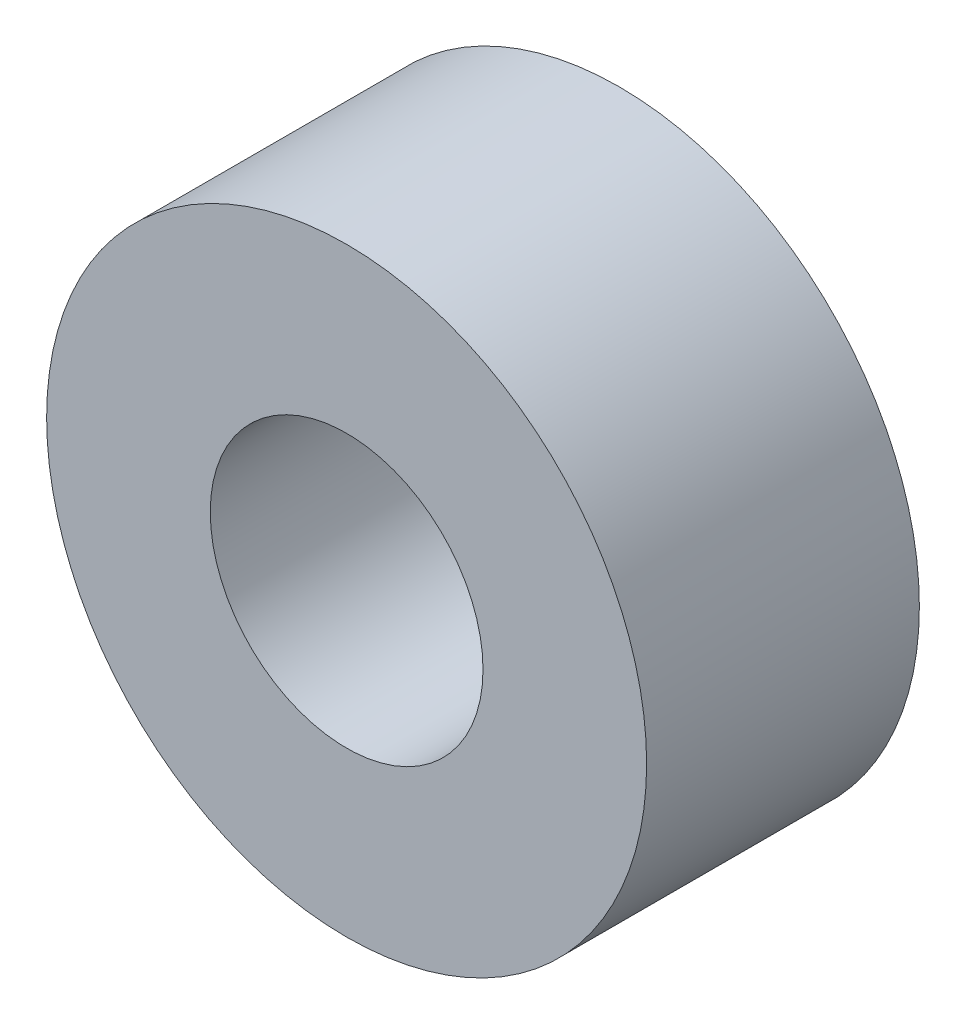
SolidWorks part; units mm, degrees
ref_plane "Front" through (0, 0, 0) normal (0, 0, 1) x (1, 0, 0)
ref_plane "Top" through (0, 0, 0) normal (0, 1, 0) x (1, 0, 0)
ref_plane "Right" through (0, 0, 0) normal (1, 0, 0) x (0, 0, -1)
sketch "Sketch1" plane through (0, 0, 0) normal (0, 0, 1) x (1, 0, 0)
  circle A0 centre (0, 0) radius 2.5
  circle A1 centre (0, 0) radius 5.5
  dimension "D1" = 5
  dimension "D2" = 11
extrude "Boss-Extrude1" add sketch "Sketch1" along normal blind 5
